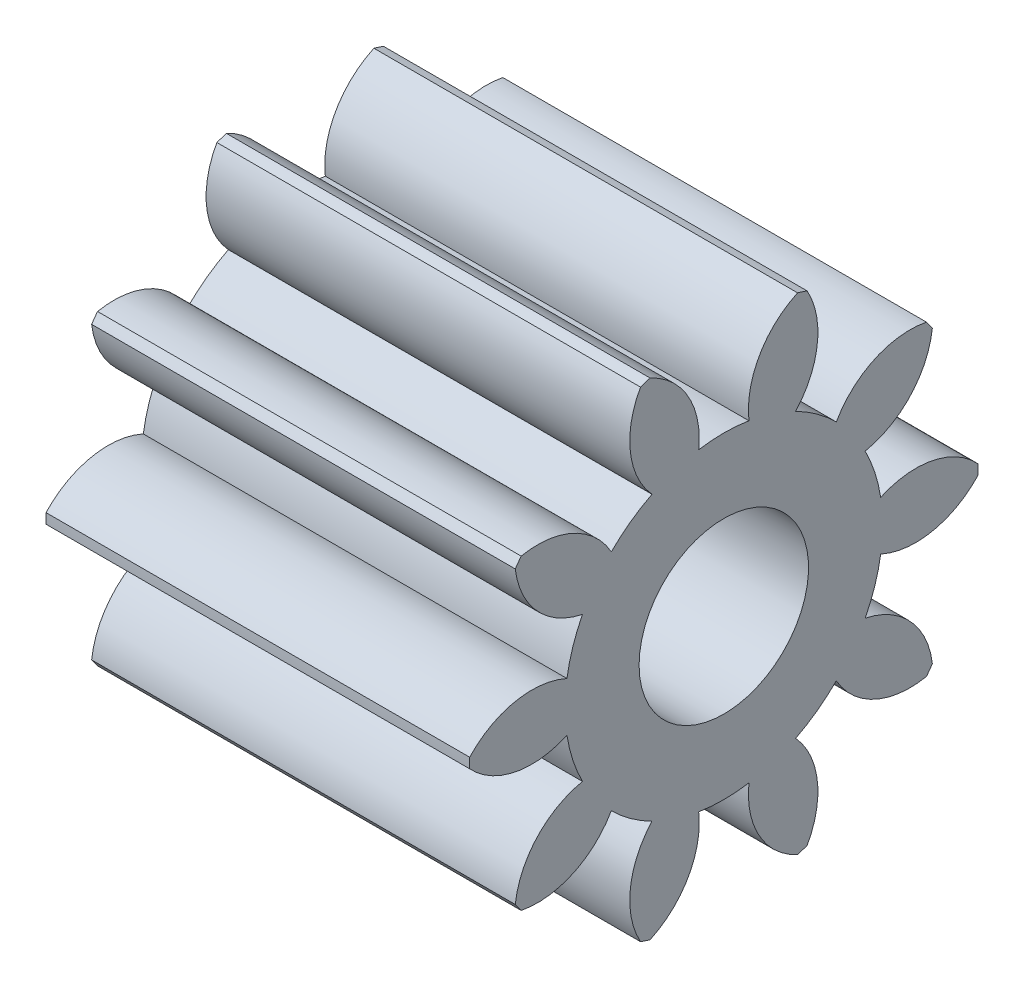
SolidWorks part; units mm, degrees
ref_plane "Plane1" through (0, 0, 0) normal (0, 0, 1) x (1, 0, 0)
ref_plane "Plane2" through (0, 0, 0) normal (0, 1, 0) x (1, 0, 0)
ref_plane "Plane3" through (0, 0, 0) normal (1, 0, 0) x (0, 0, -1)
sketch "HoldingSke" plane through (0, 0, 0) normal (0, 1, 0) x (1, 0, 0)
  line L0 (0, 0) -> (1.9696, -0.3473)
  line L1 (-15, 0) -> (100, 0) construction
  line L2 (0, 0) -> (-2.1039, 2.3779)
  line L3 (0, 0) -> (-11.863, 4.5341)
  line L4 (0, 0) -> (8.5048, 1.4996)
  line L5 (0, 0) -> (-46.8476, -17.4728)
  line L6 (0, 0) -> (-4.1448, -2.7965)
  line L7 (-2.1039, 2.3779) -> (8.6586, 51.2059)
  line L8 (-76.2, 54.61) -> (-75.9, 54.61)
  line L9 (-71.009, 38.7566) -> (-53.1078, 45.2721)
  line L10 (-76.2, 71.12) -> (104.1128, 71.12)
  line L11 (0, 0) -> (-5, 0)
  line L12 (-76.2, 101.6) -> (-76.181, 101.6)
  line L13 (24.9733, 27.94) -> (52.9518, 28.4284)
  line L14 (24.9733, 27.94) -> (24.9743, 27.94)
  line L15 (24.9733, 27.94) -> (100.4006, 29.5858)
  line L16 (-63.627, -0.5) -> (-12.827, -0.5)
  circle A0 centre (0, 0) radius 1
  circle A1 centre (0, 0) radius 1.874
  circle A2 centre (0, 0) radius 37.5
  circle A3 centre (0, 0) radius 1
  dimension "MHD" = 3.748
  dimension "Hub_dia" = 75
  dimension "Bore" = 2
  dimension "MBD" = 2
  dimension "Num_teeth" = 10
  dimension "Pitch" = 2
  dimension "Overall_len" = 50
  dimension "Show_teeth" = 10
  dimension "Thickness" = 5
  dimension "OAL" = 50.0001
  dimension "T_dim" = 0.3
  dimension "Ap" = 20
  dimension "H" = 19.05
  dimension "Pitch_radius" = 180.3128
  dimension "Width" = 5
  dimension "Backlash" = 0.019
  dimension "Addendum_fac" = 1
  dimension "Dedendum_fac" = 1.25
  dimension "Clearance_fac" = 0.25
  dimension "Dedendum_add" = 0.001
  dimension "Module" = 0.5
sketch "BasProSke" plane through (0, 0, 0) normal (0, 1, 0) x (1, 0, 0)
  line L0 (-10, 0) -> (60, 0) construction
  line L1 (0, 0) -> (0, 3)
  line L2 (0, 0) -> (5, 0)
  line L3 (5, 0) -> (5, 3)
  line L4 (5, 3) -> (0, 3)
  dimension "Thickness" = 5
  dimension "Diameter" = 6
revolve "Base-Revolve" add sketch "BasProSke" angle 360 about L0
sketch "TooCutSke" plane through (0, 0, 0) normal (1, 0, 0) x (0, 0, -1)
  line L1 (0, 0) -> (0, 107) construction
  line L2 (0, 0) -> (-0.4243, 2.4637) construction
  line L3 (0, 0) -> (-1.5292, 4.7063) construction
  line L4 (-0.4243, 2.4637) -> (-0.7646, 2.3532) construction
  arc A0 (0.2964, 1.8504) -> (-0.2964, 1.8504) centre (0, 0) ccw
  arc A1 (0.9059, 2.8866) -> (-0.9059, 2.8866) centre (0, 0) ccw
  circle A2 centre (0, 0) radius 2.5 construction
  circle A3 centre (0, 0) radius 2.3492 construction
  arc A4 (-0.2964, 1.8504) -> (-0.9059, 2.8866) centre (-1.2901, 1.9633) ccw
  arc A5 (0.9059, 2.8866) -> (0.2964, 1.8504) centre (1.2901, 1.9633) ccw
  dimension "Root_dia" = 3.748
  dimension "Overcut_dia" = 6.0508
  dimension "Pitch_dia" = 5
  dimension "Base_dia" = 4.6985
  dimension "Flank_rad" = 1
  dimension "Half_ang" = 18
  dimension "Half_CT" = 0.3578
extrude "ToothCut" cut sketch "TooCutSke" along normal through all
fillet "Breaks" [suppressed] radius 0.01
fillet "RootFillets" [suppressed] radius 0.126
pattern_circular "TeethCuts" count 10 every 36 about axis through (-10, 0, 0) along (1, 0, 0) of "ToothCut", "RootFillets", "Breaks"
sketch "HubNeaOneSke" plane through (0, 0, 0) normal (-1, 0, 0) x (0, 0, 1)
  circle A0 centre (0, 0) radius 1.874
  dimension "Diameter" = 3.748
extrude "HubNearOne" [suppressed] add sketch "HubNeaOneSke" along normal blind 45.0001
sketch "HubNeaBotSke" plane through (0, 0, 0) normal (-1, 0, 0) x (0, 0, 1)
  circle A0 centre (0, 0) radius 1.874
  dimension "Diameter" = 3.748
extrude "HubNearBoth" [suppressed] add sketch "HubNeaBotSke" along normal blind 22.5
ref_plane "FarPln" through (5, 0, 0) normal (1, 0, 0) x (0, 0, -1)
sketch "HubFarSke" plane through (5, 0, 0) normal (1, 0, 0) x (0, 0, -1)
  circle A0 centre (0, 0) radius 1.874
  dimension "Diameter" = 3.748
extrude "HubFar" [suppressed] add sketch "HubFarSke" along normal blind 22.5
sketch "BorSke" plane through (0, 0, 0) normal (1, 0, 0) x (0, 0, -1)
  circle A0 centre (0, 0) radius 1
  dimension "Diameter" = 2
extrude "Bore" cut sketch "BorSke" along normal mid plane 100.0001
sketch "KeySke" plane through (0, 0, 0) normal (1, 0, 0) x (0, 0, -1)
  line L0 (-0.4, 0) -> (-0.4, 1.3)
  line L1 (-0.4, 1.3) -> (0.4, 1.3)
  line L2 (0.4, 1.3) -> (0.4, 0)
  line L3 (0, 0) -> (0, 34) construction
  line L4 (-0.4, 0) -> (0.4, 0)
  dimension "Offset" = 1.3
  dimension "Width" = 0.8
extrude "Keyway" [suppressed] cut sketch "KeySke" along normal mid plane 100.0001
pattern_circular "Keyway2" [suppressed] count 2 every 90 about axis through (-10, 0, 0) along (1, 0, 0)
ref_plane "Plan1" through (2.5, 0, 0) normal (1, 0, 0) x (0, 0, -1)
equation "' \"Module@HoldingSke\" = 6.35"
equation "' \"Num_teeth@HoldingSke\" = 12"
equation "' \"Ap@HoldingSke\" =  20"
equation "' \"Ap@HoldingSke\" = 20"
equation "' \"Width@HoldingSke\" = 0.5 * 25.4"
equation "' \"Hub_dia@HoldingSke\"= 1 * 25.4"
equation "' \"Hub_dia@HoldingSke\" = 1 * 25.4"
equation "' \"Overall_len@HoldingSke\" = 1.0 * 25.4"
equation "' \"Bore@HoldingSke\" = 0.75 * 25.4"
equation "' \"T_dim@HoldingSke\" = 0.1 * 25.4"
equation "' \"Width@KeySke\" = 0.25 * 25.4"
equation "' \"Show_teeth@HoldingSke\" = 13"
equation "' \"Backlash@HoldingSke\" = 0.009 * 25.4"
equation "' \"Addendum_fac@HoldingSke\" = 1.0"
equation "' \"Dedendum_fac@HoldingSke\" = 1.25"
equation "' \"Dedendum_add@HoldingSke\" = 0.00005 * 25.4"
equation "' \"Clearance_fac@HoldingSke\" = 0.25"
equation "\"Pitch@HoldingSke\" = 1 / \"Module@HoldingSke\""
equation "\"Overcut_dia@TooCutSke\" = (\"Num_teeth@HoldingSke\" + 2 * \"Addendum_fac@HoldingSke\") / \"Pitch@HoldingSke\" + 0.002 * 25.4"
equation "\"Pitch_dia@TooCutSke\" = \"Num_teeth@HoldingSke\" / \"Pitch@HoldingSke\""
equation "\"Base_dia@TooCutSke\" = \"Num_teeth@HoldingSke\" / \"Pitch@HoldingSke\" * cos((\"Ap@HoldingSke\"  * 3.14159265 / 180))"
equation "\"Root_dia@TooCutSke\" = (\"Num_teeth@HoldingSke\" + 2) / \"Pitch@HoldingSke\" - 2 * (\"Addendum_fac@HoldingSke\" + \"Dedendum_fac@HoldingSke\") / \"Pitch@HoldingSke\" - \"Dedendum_add@HoldingSke\" * 2"
equation "\"Half_ang@TooCutSke\" = 180 / \"Num_teeth@HoldingSke\""
equation "\"Half_CT@TooCutSke\" = \"Num_teeth@HoldingSke\" / \"Pitch@HoldingSke\" * sin((3.14159265 / 2 / \"Num_teeth@HoldingSke\")) / 2 - 7 * \"Backlash@HoldingSke\" / 4"
equation "\"Flank_rad@TooCutSke\" = \"Num_teeth@HoldingSke\" / \"Pitch@HoldingSke\" / 5"
equation "\"Radius@RootFillets\" = \"Clearance_fac@HoldingSke\" / \"Pitch@HoldingSke\" + \"Dedendum_add@HoldingSke\""
equation "\"Break_rad@Breaks\" = 0.02 / \"Pitch@HoldingSke\""
equation "\"Thickness@HoldingSke\" = \"Width@HoldingSke\""
equation "\"OAL@HoldingSke\" = \"Thickness@HoldingSke\""
equation "\"MHD@HoldingSke\" = (\"Num_teeth@HoldingSke\" + 2) / \"Pitch@HoldingSke\" - 2 * (\"Addendum_fac@HoldingSke\" + \"Dedendum_fac@HoldingSke\")  / \"Pitch@HoldingSke\" - \"Dedendum_add@HoldingSke\" * 2"
equation "\"MBD@HoldingSke\" = (\"Num_teeth@HoldingSke\" + 2) / \"Pitch@HoldingSke\" - 2 * (\"Addendum_fac@HoldingSke\" + \"Dedendum_fac@HoldingSke\")  / \"Pitch@HoldingSke\" - \"Dedendum_add@HoldingSke\" * 2 - 0.002 * 25.4"
equation "\"MHD@HoldingSke\" = ((sgn( \"MHD@HoldingSke\" - \"Hub_dia@HoldingSke\" )-1)*( \"MHD@HoldingSke\" - \"Hub_dia@HoldingSke\" ))/-2+ \"Hub_dia@HoldingSke\""
equation "\"MBD@HoldingSke\" = ((sgn( \"MBD@HoldingSke\" - \"Bore@HoldingSke\" )-1)*( \"MBD@HoldingSke\" - \"Bore@HoldingSke\" ))/-2+ \"Bore@HoldingSke\""
equation "\"OAL@HoldingSke\" = ((sgn( \"OAL@HoldingSke\" - \"Overall_len@HoldingSke\" )+1)*( \"OAL@HoldingSke\" - \"Overall_len@HoldingSke\" ))/2 + \"Overall_len@HoldingSke\" + 0.000002 * 25.4"
equation "\"Num_teeth@TeethCuts\" = int( \"Show_teeth@HoldingSke\" ) + 1"
equation "\"Num_teeth@TeethCuts\" = ((sgn( \"Num_teeth@TeethCuts\" - \"Num_teeth@HoldingSke\" )-1)*( \"Num_teeth@TeethCuts\" - \"Num_teeth@HoldingSke\" ))/-2+ \"Num_teeth@HoldingSke\""
equation "\"Num_teeth@TeethCuts\" = ((sgn( \"Num_teeth@TeethCuts\" - 2.0)+1)*( \"Num_teeth@TeethCuts\" - 2.0))/2 +2.0"
equation "\"Angle@TeethCuts\" = 360.0 / \"Num_teeth@HoldingSke\""
equation "\"Diameter@BasProSke\" = (\"Num_teeth@HoldingSke\" + 2 * \"Addendum_fac@HoldingSke\") / \"Pitch@HoldingSke\""
equation "\"Thickness@BasProSke\"  = \"Thickness@HoldingSke\""
equation "' \"Fillet_rad@BasProSke\" =  \"Thickness@HoldingSke\" * 0.05"
equation "' \"Fillet_rad@BasProSke\" = \"Thickness@HoldingSke\" * 0.05"
equation "\"MHD@HoldingSke\" = ((sgn( \"MHD@HoldingSke\" - \"Root_dia@TooCutSke\" )-1)*( \"MHD@HoldingSke\" - \"Root_dia@TooCutSke\" ))/-2+ \"Root_dia@TooCutSke\""
equation "\"Diameter@HubNeaOneSke\" = \"MHD@HoldingSke\""
equation "\"Length@HubNearOne\" = \"OAL@HoldingSke\" - \"Thickness@BasProSke\""
equation "\"Diameter@HubNeaBotSke\" = \"MHD@HoldingSke\""
equation "\"Length@HubNearBoth\" = ( \"OAL@HoldingSke\" - \"Thickness@BasProSke\" ) / 2.0"
equation "\"Thickness@FarPln\" = \"Thickness@BasProSke\""
equation "\"Diameter@HubFarSke\" = \"MHD@HoldingSke\""
equation "\"Length@HubFar\" = ( \"OAL@HoldingSke\" - \"Thickness@BasProSke\" ) / 2.0"
equation "\"Diameter@BorSke\" = \"MBD@HoldingSke\""
equation "\"D1@Bore\" = \"OAL@HoldingSke\" * 2.0"
equation "\"D1@Keyway\" = \"OAL@HoldingSke\" * 2.0"
equation "\"Offset@KeySke\" = \"T_dim@HoldingSke\" + \"MBD@HoldingSke\" / 2.0"
